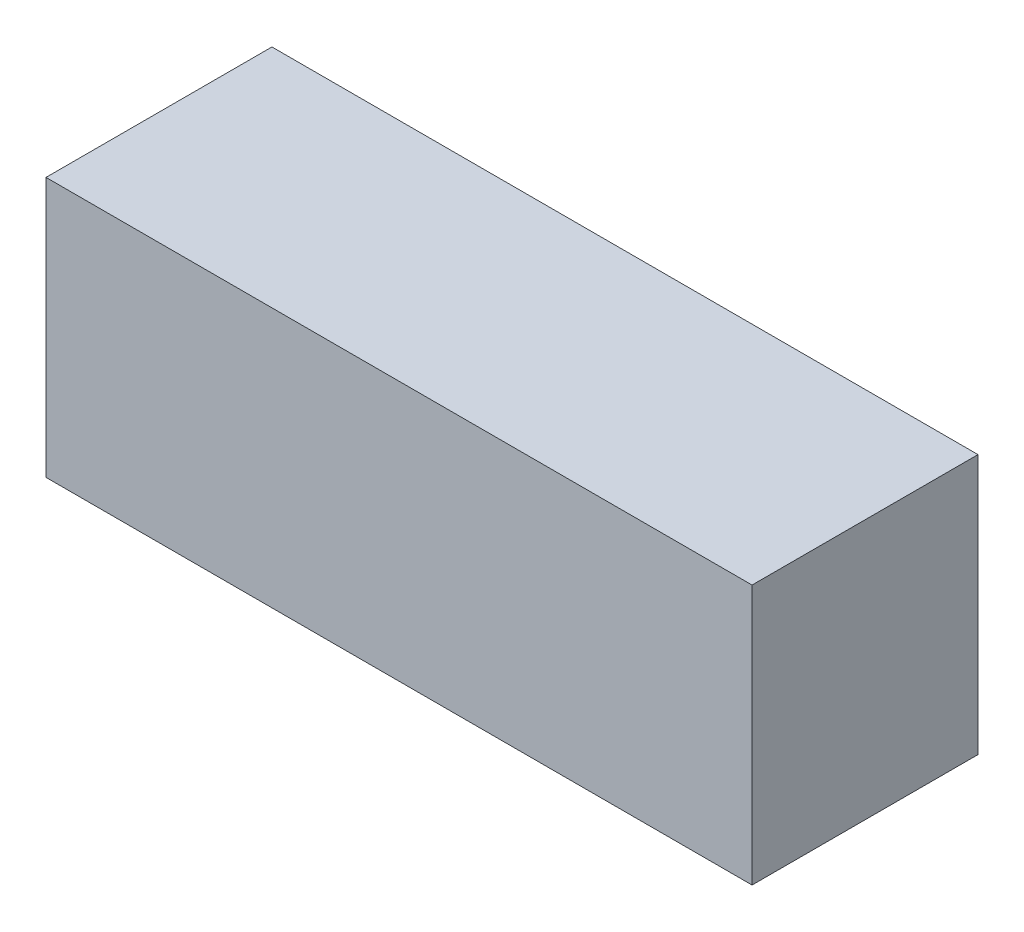
SolidWorks part; units mm, degrees
material "Custom Plastic"
ref_plane "Front Plane" through (0, 0, 0) normal (0, 0, 1) x (1, 0, 0)
ref_plane "Top Plane" through (0, 0, 0) normal (0, 1, 0) x (1, 0, 0)
ref_plane "Right Plane" through (0, 0, 0) normal (1, 0, 0) x (0, 0, -1)
sketch "Sketch1" plane through (0, 0, 0) normal (0, 0, 1) x (1, 0, 0)
  line L0 (-91.1608, -3.8) -> (-104.0608, -3.8) construction
  line L1 (-103.8608, -4) -> (-91.3608, -4)
  line L2 (-103.8608, -4) -> (-103.8608, -8.6)
  line L3 (-103.8608, -8.6) -> (-91.3608, -8.6)
  line L4 (-91.3608, -4) -> (-91.3608, -8.6)
  line L5 (-91.1608, -8.8) -> (-91.1608, -3.8) construction
  line L6 (-104.0608, -3.8) -> (-104.0608, -8.8) construction
  point P6 (-97.6108, -3.8)
  point P7 (-97.6108, -4)
  point P10 (-91.1608, -6.3)
  point P11 (-91.3608, -6.3)
  dimension "D1" = 0.2
  dimension "D2" = 0.2
extrude "Boss-Extrude1" add sketch "Sketch1" against normal blind 4
